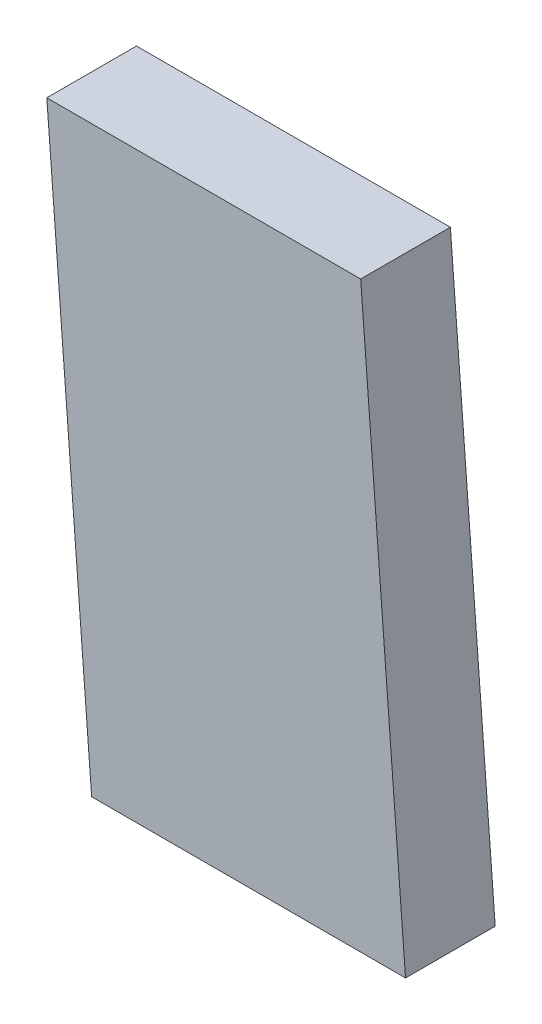
SolidWorks part; units mm, degrees
ref_plane "Front Plane" through (0, 0, 0) normal (0, 0, 1) x (1, 0, 0)
ref_plane "Top Plane" through (0, 0, 0) normal (0, 1, 0) x (1, 0, 0)
ref_plane "Right Plane" through (0, 0, 0) normal (1, 0, 0) x (0, 0, -1)
sketch "Sketch1" plane through (0, 0, 0) normal (0, 0, 1) x (1, 0, 0)
  line L0 (4500, 450) -> (4490, 580)
  line L1 (4490, 580) -> (4560, 580)
  line L2 (4560, 580) -> (4570, 450)
  line L3 (4570, 450) -> (4500, 450)
extrude "Boss-Extrude1" add sketch "Sketch1" along normal blind 20
